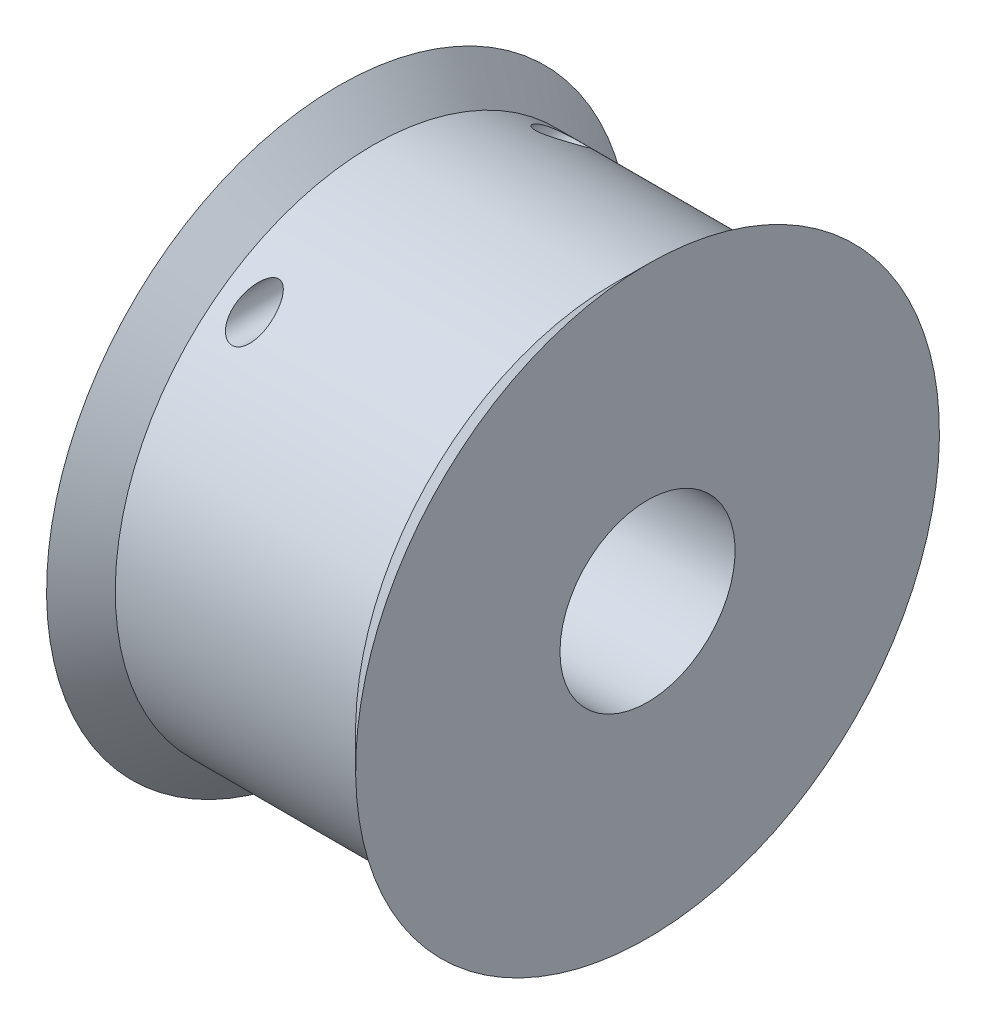
SolidWorks part; units mm, degrees
ref_plane "Plan de face" through (0, 0, 0) normal (0, 0, 1) x (1, 0, 0)
ref_plane "Plan de dessus" through (0, 0, 0) normal (0, 1, 0) x (1, 0, 0)
ref_plane "Plan de droite" through (0, 0, 0) normal (1, 0, 0) x (0, 0, -1)
sketch "Esquisse1" plane through (0, 0, 0) normal (0, 0, 1) x (1, 0, 0)
  line L0 (9, 0) -> (9, 17)
  line L1 (9, 17) -> (7, 15)
  line L2 (7, 15) -> (-7, 15)
  line L3 (0, 15) -> (0, 0) construction
  line L4 (-9, 0) -> (9, 0) construction
  line L5 (-9, 17) -> (-7, 15)
  line L6 (-9, 0) -> (-9, 17)
  line L7 (9, 0) -> (-9, 0)
  dimension "D1" = 18
  dimension "D2" = 30
  dimension "D3" = 45
  dimension "D4" = 14
revolve "Révolution1" add sketch "Esquisse1" angle 360 about L7
sketch "Esquisse2" plane through (-9, 0, 0) normal (-1, 0, 0) x (0, 0, 1)
  circle A0 centre (0, 0) radius 5.1
  dimension "D1" = 10.2
extrude "Enlèv. mat.-Extru.1" cut sketch "Esquisse2" against normal through all both and the other way through all
sketch "Esquisse3" plane through (0, 0, 0) normal (0, 0, 1) x (1, 0, 0)
  circle A0 centre (-5, 12) radius 1
  dimension "D1" = 12
  dimension "D2" = 5
  dimension "D3" = 2
extrude "Enlèv. mat.-Extru.2" cut sketch "Esquisse3" against normal through all both and the other way through all
sketch "Esquisse4" plane through (0, 0, 0) normal (0, 0, 1) x (1, 0, 0)
  circle A0 centre (0, 0) radius 1.65
  dimension "D1" = 3.3
extrude "Enlèv. mat.-Extru.3" cut sketch "Esquisse4" against normal through all
